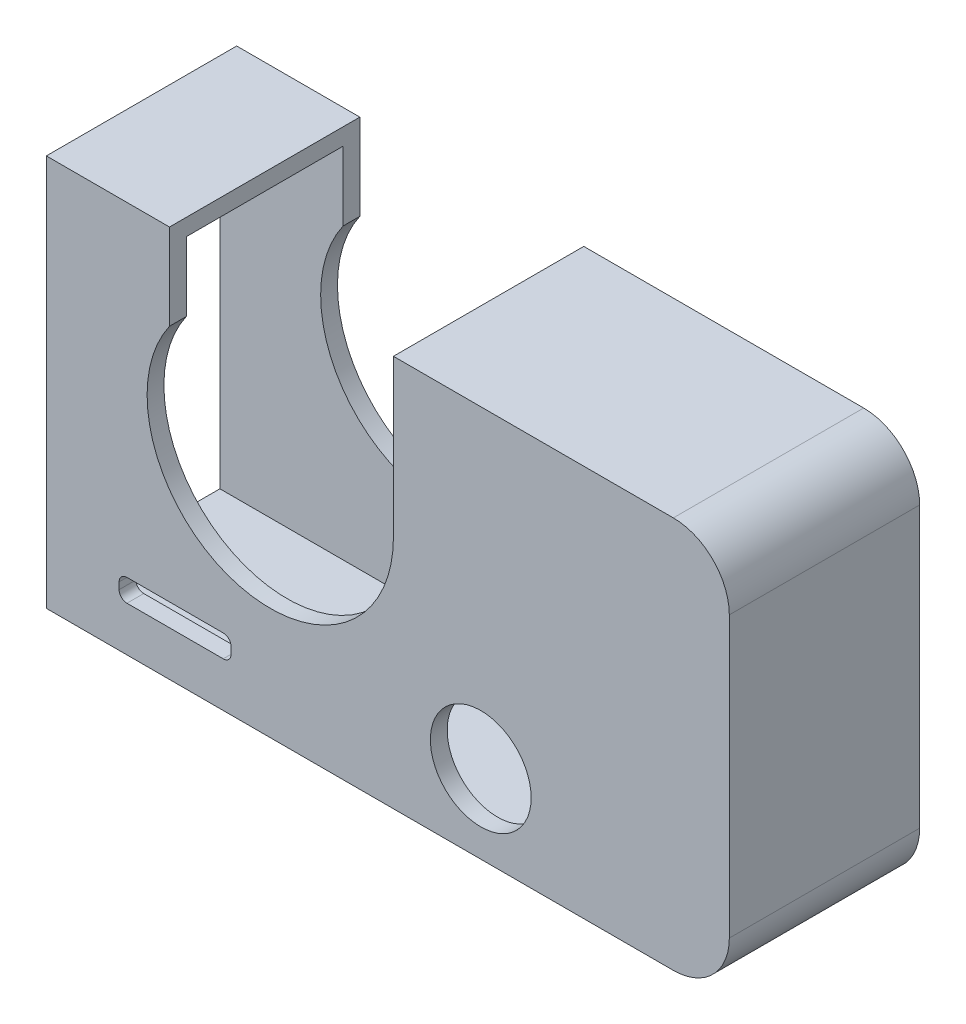
SolidWorks part; units mm, degrees
ref_plane "Front Plane" through (0, 0, 0) normal (0, 0, 1) x (1, 0, 0)
ref_plane "Top Plane" through (0, 0, 0) normal (0, 1, 0) x (1, 0, 0)
ref_plane "Right Plane" through (0, 0, 0) normal (1, 0, 0) x (0, 0, -1)
sketch "Sketch1" plane through (0, 0, 0) normal (0, 0, 1) x (1, 0, 0)
  line L0 (0, 21) -> (61, 21) construction
  line L1 (0, 0) -> (56, 0)
  line L2 (0, 0) -> (0, 35)
  line L3 (0, 35) -> (11, 35)
  line L4 (61, 5) -> (61, 30)
  line L5 (20, 35) -> (20, 0) construction
  line L6 (31, 21) -> (31, 35)
  line L7 (11, 27.3246) -> (11, 35)
  line L8 (31, 35) -> (56, 35)
  line L9 (0, 30) -> (61, 30) construction
  line L10 (0, 5) -> (61, 5) construction
  arc A0 (11, 27.3246) -> (31, 21) centre (20, 21) ccw
  arc A1 (56, 0) -> (61, 5) centre (56, 5) ccw
  arc A2 (61, 30) -> (56, 35) centre (56, 30) ccw
  arc A3 (11, 27.3246) -> (31, 21) centre (20, 21) ccw
  point P22 (61, 0)
  dimension "D5" = 22
  dimension "D9" = 5
  dimension "D8" = 21
  dimension "D1" = 35
  dimension "D2" = 30
  dimension "D3" = 5
  dimension "D4" = 20
  dimension "D6" = 20
  dimension "D7" = 5
extrude "Boss-Extrude2" add sketch "Sketch1" along normal blind 17 contours L4 A2 L8 L6 A0 L7 L3 L2 L1 A1
ref_plane "Plane1" through (0, 0, 1.5) normal (0, 0, -1) x (-1, 0, 0)
sketch "Sketch5" plane through (0, 0, 1.5) normal (0, 0, -1) x (-1, 0, 0)
  line L0 (-54.5, 33.5) -> (-1.5, 33.5)
  line L2 (-1.5, 33.5) -> (-1.5, 1.5)
  line L3 (-1.5, 1.5) -> (-54.5, 1.5)
  line L4 (-59.5, 6.5) -> (-59.5, 28.5)
  line L5 (0, 35) -> (-11, 35) construction
  line L6 (0, 0) -> (0, 35) construction
  line L7 (0, 0) -> (-56, 0) construction
  line L8 (-61, 5) -> (-61, 30) construction
  arc A0 (-54.5, 1.5) -> (-59.5, 6.5) centre (-54.5, 6.5) cw
  arc A1 (-54.5, 33.5) -> (-59.5, 28.5) centre (-54.5, 28.5) ccw
  dimension "D5" = 5
  dimension "D1" = 1.5
  dimension "D2" = 1.5
  dimension "D3" = 1.5
  dimension "D4" = 1.5
extrude "Cut-Extrude1" cut sketch "Sketch5" against normal blind 14
sketch "Sketch9" plane through (0, 0, 0) normal (-1, 0, 0) x (0, 0, 1)
  line L0 (1.5, 19.25) -> (1.5, -19.25) construction
  line L1 (1.5, 33.5) -> (15.5, 33.5)
  line L2 (1.5, 33.5) -> (1.5, 1.5)
  line L3 (1.5, 1.5) -> (15.5, 1.5)
  line L4 (15.5, 33.5) -> (15.5, 1.5)
  line L6 (17, 35) -> (0, 35) construction
  line L7 (17, 0) -> (17, 35) construction
  line L8 (17, 0) -> (0, 0) construction
  dimension "D1" = 1.5
  dimension "D2" = 1.5
  dimension "D3" = 1.5
sketch "Sketch10" plane through (0, 0, 17) normal (0, 0, 1) x (1, 0, 0)
  line L0 (0, 0) -> (56, 0) construction
  line L1 (7.2, 4) -> (15.8, 4)
  line L2 (6.5, 4.7) -> (6.5, 5.3)
  line L3 (7.2, 6) -> (15.8, 6)
  line L4 (16.5, 4.7) -> (16.5, 5.3)
  line L6 (0, 0) -> (0, 35) construction
  arc A0 (16.5, 4.7) -> (15.8, 4) centre (15.8, 4.7) cw
  arc A1 (16.5, 5.3) -> (15.8, 6) centre (15.8, 5.3) ccw
  arc A2 (6.5, 4.7) -> (7.2, 4) centre (7.2, 4.7) ccw
  arc A3 (7.2, 6) -> (6.5, 5.3) centre (7.2, 5.3) ccw
  point P10 (16.5, 4)
  point P15 (6.5, 4)
  point P18 (6.5, 6)
  dimension "D5" = 0.7
  dimension "D1" = 6
  dimension "D2" = 16.5
  dimension "D3" = 10
  dimension "D4" = 2
extrude "Cut-Extrude3" cut sketch "Sketch10" against normal blind 5
extrude "Cut-Extrude4" cut sketch "Sketch9" against normal blind 11
sketch "Sketch11" plane through (0, 0, 17) normal (0, 0, 1) x (1, 0, 0)
  line L0 (38.8, 35) -> (38.8, 0) construction
  line L1 (31, 35) -> (56, 35) construction
  line L2 (0, 0) -> (56, 0) construction
  line L4 (31, 21) -> (31, 35) construction
  line L5 (61, 7) -> (38.8, 7) construction
  line L6 (61, 5) -> (61, 30) construction
  circle A0 centre (38.8, 7) radius 4.5
  dimension "D3" = 9
  dimension "D1" = 7.8
  dimension "D2" = 7
extrude "Cut-Extrude5" cut sketch "Sketch11" against normal blind 10.5
